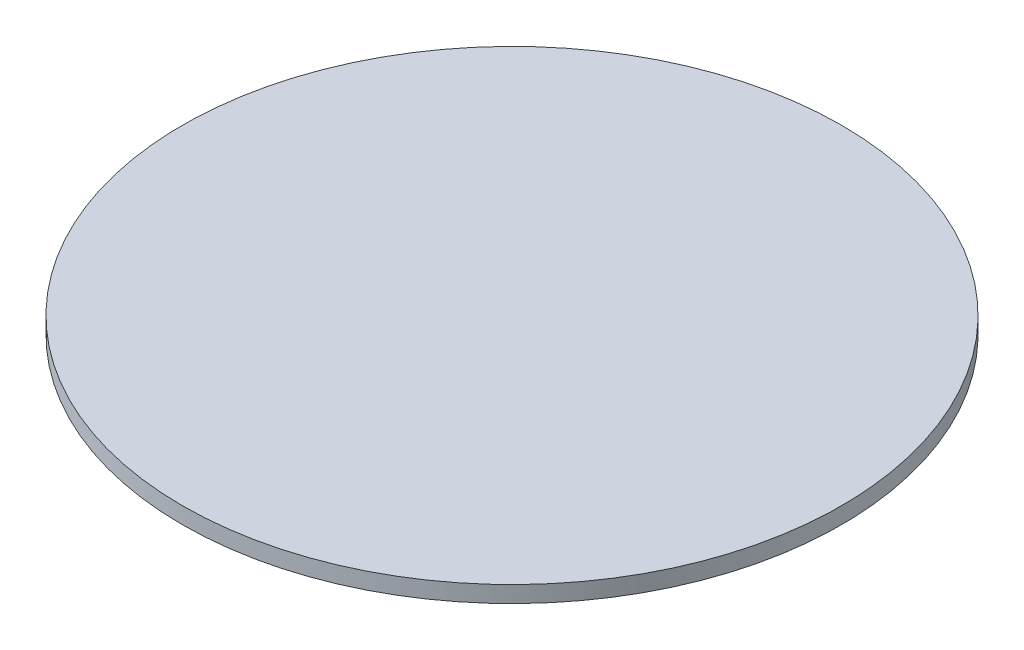
SolidWorks part; units mm, degrees
ref_plane "Front Plane" through (0, 0, 0) normal (0, 0, 1) x (1, 0, 0)
ref_plane "Top Plane" through (0, 0, 0) normal (0, 1, 0) x (1, 0, 0)
ref_plane "Right Plane" through (0, 0, 0) normal (1, 0, 0) x (0, 0, -1)
sketch "Sketch1" plane through (0, 0, 0) normal (0, 1, 0) x (1, 0, 0)
  circle A0 centre (0, 0) radius 101.6
  dimension "D1" = 203.2
extrude "Boss-Extrude1" add sketch "Sketch1" along normal mid plane 5.08 contours A0
